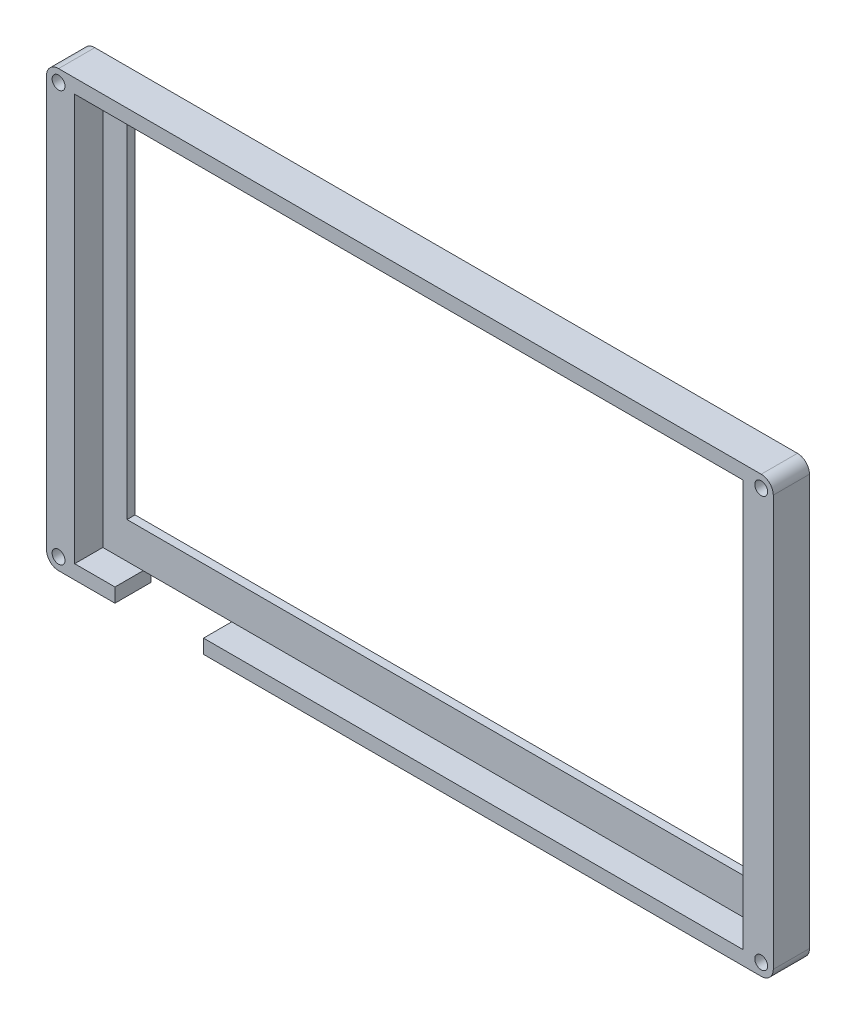
SolidWorks part; units mm, degrees
ref_plane "前视基准面" through (0, 0, 0) normal (0, 0, 1) x (1, 0, 0)
ref_plane "上视基准面" through (0, 0, 0) normal (0, 1, 0) x (1, 0, 0)
ref_plane "右视基准面" through (0, 0, 0) normal (1, 0, 0) x (0, 0, -1)
other "Configuration Table"
sketch "草图1" plane through (0, 0, 0) normal (0, 0, 1) x (1, 0, 0)
  line L2 (3, 0) -> (177.5, 0)
  line L3 (0, 3) -> (0, 105)
  line L4 (3, 108) -> (177.5, 108)
  line L5 (180.5, 3) -> (180.5, 105)
  arc A0 (3, 0) -> (0, 3) centre (3, 3) cw
  arc A1 (177.5, 0) -> (180.5, 3) centre (177.5, 3) ccw
  arc A2 (180.5, 105) -> (177.5, 108) centre (177.5, 105) ccw
  arc A3 (0, 105) -> (3, 108) centre (3, 105) cw
  circle A4 centre (3, 3) radius 1.6
  circle A5 centre (3, 105) radius 1.6
  circle A6 centre (177.5, 105) radius 1.6
  circle A7 centre (177.5, 3) radius 1.6
  point P6 (0, 0)
  point P18 (0, 54)
  point P19 (180.5, 54)
  dimension "D1" = 3
  dimension "D2" = 180.5
  dimension "D3" = 108
extrude "凸台-拉伸3" add sketch "草图1" along normal blind 9
sketch "草图3" plane through (0, 0, 9) normal (0, 0, 1) x (1, 0, 0)
  line L0 (177.5, 108) -> (3, 108) construction
  line L1 (7, 104.5) -> (173, 104.5)
  line L2 (7, 104.5) -> (7, 3.5)
  line L3 (7, 3.5) -> (173, 3.5)
  line L4 (173, 104.5) -> (173, 3.5)
  line L5 (3, 0) -> (177.5, 0) construction
  line L6 (0, 105) -> (0, 3) construction
  dimension "D1" = 3.5
  dimension "D2" = 3.5
  dimension "D3" = 166
  dimension "D4" = 7
extrude "切除-拉伸1" cut sketch "草图3" against normal blind 7 contours L2 L3 L4 L1
sketch "草图5" plane through (0, 0, 2) normal (0, 0, 1) x (1, 0, 0)
  line L0 (173, 104.5) -> (173, 3.5) construction
  line L1 (13, 100.5) -> (170, 100.5)
  line L2 (13, 100.5) -> (13, 12.5)
  line L3 (13, 12.5) -> (170, 12.5)
  line L4 (170, 100.5) -> (170, 12.5)
  line L5 (7, 104.5) -> (173, 104.5) construction
  line L6 (7, 3.5) -> (173, 3.5) construction
  line L9 (7, 104.5) -> (7, 3.5) construction
  point P10 (0, 0)
  point P12 (12.8949, 19.4732)
  dimension "D1" = 3
  dimension "D2" = 4
  dimension "D3" = 9
  dimension "D4" = 6
extrude "切除-拉伸2" cut sketch "草图5" against normal through all
sketch "草图6" plane through (0, 0, 9) normal (0, 0, 1) x (1, 0, 0)
  line L0 (7, 3.5) -> (17, 3.5)
  line L1 (7, 3.5) -> (173, 3.5) construction
  line L2 (17, 3.5) -> (39, 3.5)
  line L3 (39, 3.5) -> (39, 0)
  line L4 (3, 0) -> (177.5, 0) construction
  line L5 (39, 0) -> (17, 0)
  line L6 (17, 0) -> (17, 3.5)
  line M8 (3, 0) -> (177.5, 0)
  line M17 (173, 3.5) -> (7, 3.5)
  dimension "D1" = 10
  dimension "D2" = 22
extrude "切除-拉伸3" cut sketch "草图6" against normal through all contours L6 L3 M8 M17
